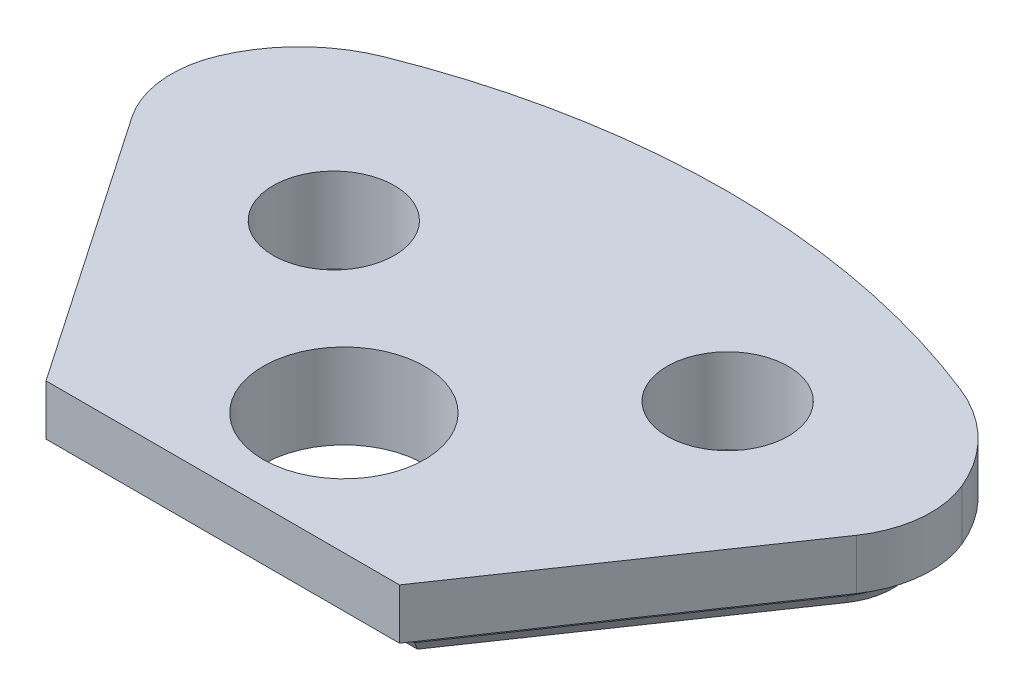
SolidWorks part; units mm, degrees
ref_plane "Спереди" through (0, 0, 0) normal (0, 0, 1) x (1, 0, 0)
ref_plane "Сверху" through (0, 0, 0) normal (0, 1, 0) x (1, 0, 0)
ref_plane "Справа" through (0, 0, 0) normal (1, 0, 0) x (0, 0, -1)
sketch "Sketch1" plane through (0, 0, 0) normal (0, 1, 0) x (1, 0, 0)
  line L0 (17.5, 0) -> (-17.5, 0)
  line L1 (0, 0) -> (0, 50) construction
  line L2 (38, 50) -> (-38, 50) construction
  line L3 (-38, 30) -> (38, 30) construction
  line L4 (-38, 30) -> (-17.5, 0)
  line L5 (17.5, 0) -> (38, 30)
  line L6 (-38, 30) -> (-38, 40)
  line L7 (38, 30) -> (38, 40)
  arc A0 (-38, 40) -> (38, 40) centre (0, -27.2) cw
  point P3 (0, 0)
  point P8 (0, 50)
  point P13 (0, 0)
  point P16 (0, 0)
  dimension "D2" = 77.2
  dimension "D1" = 35
  dimension "D3" = 10
  dimension "D4" = 50
  dimension "D5" = 76
extrude "Boss-Extrude1" add sketch "Sketch1" along normal blind 5
fillet "Fillet2" radius 15 2 edges at (38, 2.5, -40) (-38, 2.5, -40)
fillet "Fillet3" radius 10 2 edges at (38, 2.5, -30) (-38, 2.5, -30)
shell "Shell1" thickness 3.2
sketch "Sketch5" plane through (0, 1.8, 0) normal (0, -1, 0) x (1, 0, 0)
  line L0 (15.8109, -3.2) -> (-15.8109, -3.2)
  line L1 (-15.8109, -3.2) -> (-33.2264, -28.6861)
  line L2 (15.8109, -3.2) -> (33.2264, -28.6861)
  arc A0 (33.2264, -28.6861) -> (33.8843, -35.149) centre (27.612, -32.5225) cw
  arc A1 (33.8843, -35.149) -> (27.3633, -41.555) centre (23, -30.5913) cw
  arc A2 (27.3633, -41.555) -> (-27.3633, -41.555) centre (0, 27.2) cw
  arc A3 (-27.3633, -41.555) -> (-33.8843, -35.149) centre (-23, -30.5913) cw
  arc A4 (-33.8843, -35.149) -> (-33.2264, -28.6861) centre (-27.612, -32.5225) cw
extrude "Boss-Extrude2" add sketch "Sketch5" along normal blind 5.2
chamfer "Chamfer1" distance 1 angle 30 8 edges at (0, -3.4, -3.2) (-24.5186, -3.4, -15.943) (-34.377, -3.4, -31.8339) (-31.2693, -3.4, -39.0091) (0, -3.4, -46.8) (31.2693, -3.4, -39.0091) (34.377, -3.4, -31.8339) (24.5186, -3.4, -15.943)
sketch "Sketch2" plane through (0, 5, 0) normal (0, 1, 0) x (1, 0, 0)
  line L0 (-25.7, 12) -> (25.7, 12) construction
  line L1 (-35.8684, 26.8806) -> (-17.5, 0) construction
  line L2 (17.5, 0) -> (35.8684, 26.8806) construction
  line L3 (-17.5, 0) -> (17.5, 0) construction
  circle A0 centre (0, 12) radius 8
  dimension "D1" = 16
  dimension "D2" = 12
extrude "Cut-Extrude1" cut sketch "Sketch2" against normal through all
sketch "Sketch3" plane through (0, 5, 0) normal (0, 1, 0) x (1, 0, 0)
  line L0 (-36.6333, 28) -> (36.6333, 28) construction
  line L1 (-35.8684, 26.8806) -> (-17.5, 0) construction
  line L2 (17.5, 0) -> (35.8684, 26.8806) construction
  line L3 (-17.5, 0) -> (17.5, 0) construction
  line L4 (-39.3667, 32) -> (39.3667, 32) construction
  line L5 (0, 0) -> (0, 50) construction
  circle A0 centre (-17, 28) radius 6
  circle A1 centre (18, 32) radius 6
  arc A2 (28.5466, 44.5282) -> (-28.5466, 44.5282) centre (0, -27.2) ccw construction
  dimension "D1" = 12
  dimension "D2" = 28
  dimension "D3" = 17
  dimension "D4" = 32
  dimension "D5" = 18
extrude "Cut-Extrude2" cut sketch "Sketch3" against normal through all
equation "\"A\"=28"
